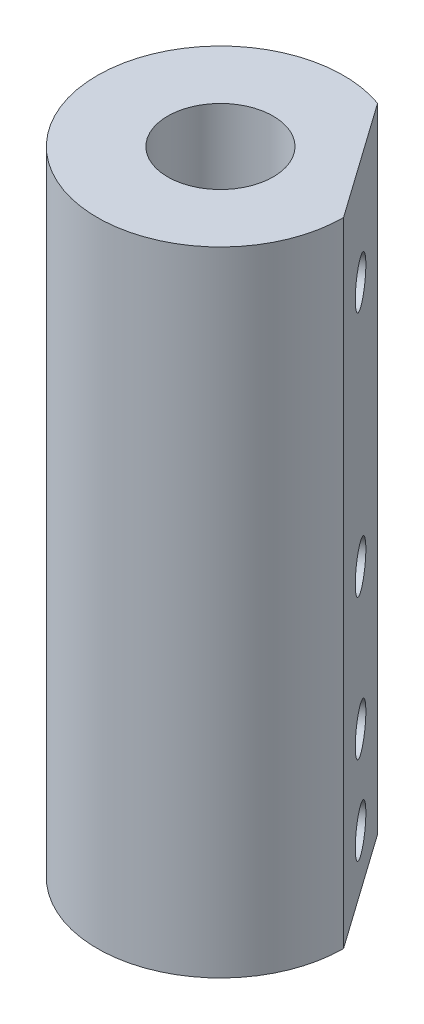
SolidWorks part; units mm, degrees
ref_plane "Front Plane" through (0, 0, 0) normal (0, 0, 1) x (1, 0, 0)
ref_plane "Top Plane" through (0, 0, 0) normal (0, 1, 0) x (1, 0, 0)
ref_plane "Right Plane" through (0, 0, 0) normal (1, 0, 0) x (0, 0, -1)
sketch "Sketch1" plane through (0, 0, 0) normal (0, 1, 0) x (1, 0, 0)
  circle A0 centre (0, 0) radius 11.1125
  circle A1 centre (0, 0) radius 3.175
  dimension "D1" = 22.225
  dimension "D2" = 6.35
extrude "Boss-Extrude1" add sketch "Sketch1" along normal blind 57.15
sketch "Sketch2" plane through (0, 57.15, 0) normal (0, 1, 0) x (1, 0, 0)
  line L0 (3.7128, 10.4739) -> (11.1125, 0)
  circle A1 centre (0, 0) radius 11.1125 construction
  point P0 (3.7128, 10.4739)
  point P1 (11.1125, 0)
extrude "Cut-Extrude2" cut sketch "Sketch2" against normal blind 57.15 and the other way through all
sketch "Sketch3" plane through (0, 57.15, 0) normal (0, 1, 0) x (1, 0, 0)
  circle A0 centre (0, 0) radius 4.7625
  dimension "D1" = 9.525
extrude "Cut-Extrude3" cut sketch "Sketch3" against normal blind 38.1
sketch "Sketch4" plane through (7.4126, 0, -5.237) normal (0.8167, 0, -0.577) x (-0.577, 0, -0.8167)
  line L0 (6.4121, 0) -> (-6.4121, 0) construction
  circle A0 centre (0, 47.625) radius 1.9844
  circle A1 centre (0, 25.4) radius 1.9844
  circle A2 centre (0, 12.7) radius 1.9844
  circle A3 centre (0, 4.7625) radius 1.9844
  point P10 (0, 0)
  dimension "D1" = 3.9688
  dimension "D2" = 3.9688
  dimension "D3" = 3.9688
  dimension "D4" = 3.9688
  dimension "D6" = 12.7
  dimension "D7" = 25.4
  dimension "D8" = 47.625
  dimension "D5" = 4.7625
extrude "Cut-Extrude4" cut sketch "Sketch4" against normal up to next
